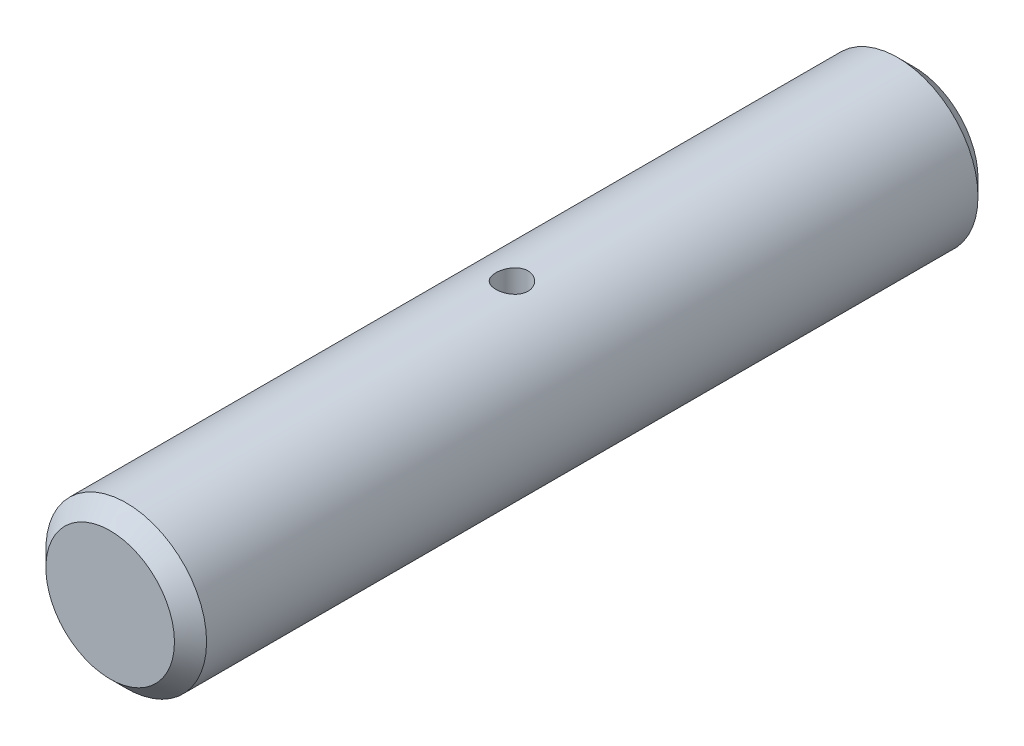
SolidWorks part; units mm, degrees
ref_plane "前视基准面" through (0, 0, 0) normal (0, 0, 1) x (1, 0, 0)
ref_plane "上视基准面" through (0, 0, 0) normal (0, 1, 0) x (1, 0, 0)
ref_plane "右视基准面" through (0, 0, 0) normal (1, 0, 0) x (0, 0, -1)
sketch "草图1" plane through (0, 0, 0) normal (0, 0, 1) x (1, 0, 0)
  circle A0 centre (0, 0) radius 5
  dimension "D1" = 10
extrude "凸台-拉伸1" add sketch "草图1" along normal mid plane 50
chamfer "倒角1" distance 1 angle 45 2 edges at (5, 0, -25) (5, 0, 25)
sketch "草图2" plane through (0, 0, 0) normal (0, 1, 0) x (1, 0, 0)
  circle A0 centre (0, 0) radius 1
  dimension "D1" = 2
extrude "切除-拉伸1" cut sketch "草图2" against normal through all both and the other way through all
